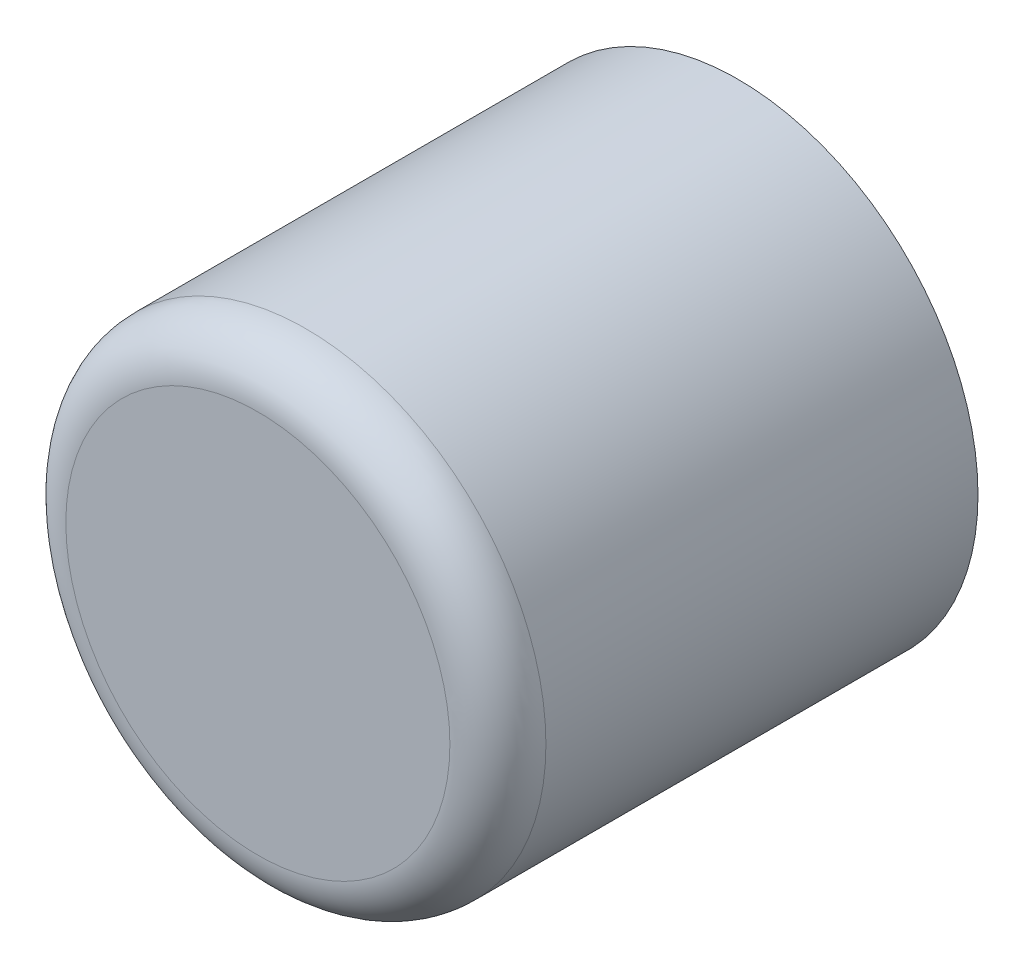
SolidWorks part; units mm, degrees
ref_plane "Front Plane" through (0, 0, 0) normal (0, 0, 1) x (1, 0, 0)
ref_plane "Top Plane" through (0, 0, 0) normal (0, 1, 0) x (1, 0, 0)
ref_plane "Right Plane" through (0, 0, 0) normal (1, 0, 0) x (0, 0, -1)
ref_plane "plane:base-xy" through (0, 0, 0) normal (0, 0, 1) x (1, 0, 0)
sketch "sketch:main-profile" plane through (0, 0, 0) normal (0, 0, 1) x (1, 0, 0)
  circle A0 centre (0, 0) radius 10
extrude "feature:cylinder" add sketch "sketch:main-profile" along normal blind 20 separate body
fillet "feature:top-fillet" radius 2 1 edges at (10, 0, 20)
